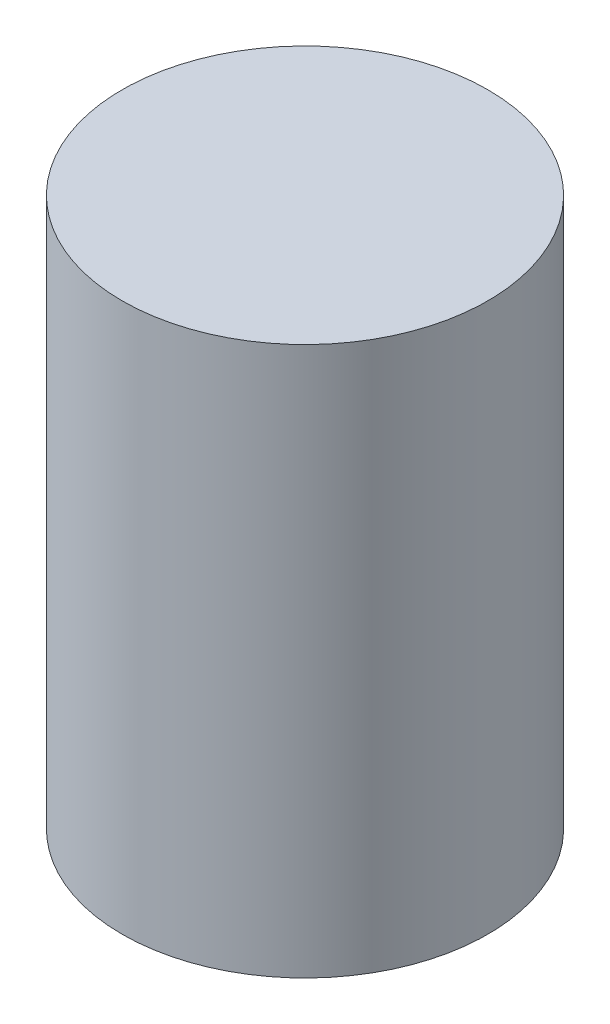
SolidWorks part; units mm, degrees
ref_plane "Front Plane" through (0, 0, 0) normal (0, 0, 1) x (1, 0, 0)
ref_plane "Top Plane" through (0, 0, 0) normal (0, 1, 0) x (1, 0, 0)
ref_plane "Right Plane" through (0, 0, 0) normal (1, 0, 0) x (0, 0, -1)
sketch "Sketch1" plane through (0, 0, 0) normal (0, 1, 0) x (1, 0, 0)
  circle A0 centre (0, 0) radius 25.4
  dimension "D1" = 50.8
extrude "Boss-Extrude1" add sketch "Sketch1" along normal blind 76.2
shell "Shell1" thickness 6.35
sketch "Sketch2" plane through (0, 0, 0) normal (0, -1, 0) x (1, 0, 0)
  circle A0 centre (0, 0) radius 9.525
  dimension "D1" = 19.05
extrude "Cut-Extrude1" cut sketch "Sketch2" against normal up to next
